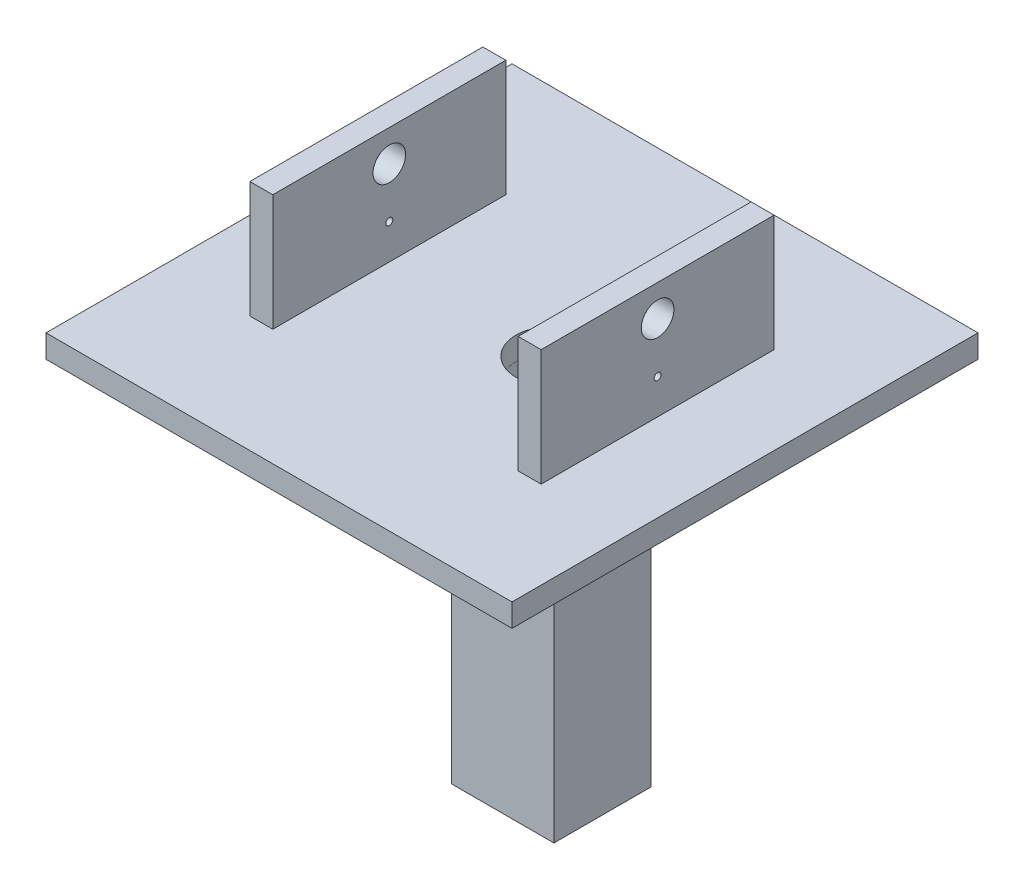
SolidWorks part; units mm, degrees
ref_plane "Front Plane" through (0, 0, 0) normal (0, 0, 1) x (1, 0, 0)
ref_plane "Top Plane" through (0, 0, 0) normal (0, 1, 0) x (1, 0, 0)
ref_plane "Right Plane" through (0, 0, 0) normal (1, 0, 0) x (0, 0, -1)
sketch "Sketch2" plane through (0, 0, 0) normal (0, 1, 0) x (1, 0, 0)
  line L1 (0, 0) -> (101.6, 0)
  line L2 (0, 0) -> (0, -101.6)
  line L3 (0, -101.6) -> (101.6, -101.6)
  line L4 (101.6, 0) -> (101.6, -101.6)
  dimension "D1" = 101.6
  dimension "D2" = 101.6
extrude "Boss-Extrude2" add sketch "Sketch2" along normal blind 5
sketch "Sketch3" plane through (0, 5, 0) normal (0, 1, 0) x (1, 0, 0)
  line L0 (0, 0) -> (0, -101.6) construction
  line L1 (19.05, -25.4) -> (24.05, -25.4)
  line L2 (19.05, -25.4) -> (19.05, -76.2)
  line L3 (19.05, -76.2) -> (24.05, -76.2)
  line L4 (24.05, -25.4) -> (24.05, -76.2)
  line L5 (0, -101.6) -> (101.6, -101.6) construction
  dimension "D1" = 5
  dimension "D2" = 19.05
  dimension "D3" = 50.8
  dimension "D4" = 25.4
extrude "Boss-Extrude3" add sketch "Sketch3" along normal blind 25.4
sketch "Sketch4" plane through (0, 5, 0) normal (0, 1, 0) x (1, 0, 0)
  line L0 (101.6, -101.6) -> (101.6, 0) construction
  line L1 (77.55, -25.4) -> (82.55, -25.4)
  line L2 (77.55, -25.4) -> (77.55, -76.2)
  line L3 (77.55, -76.2) -> (82.55, -76.2)
  line L4 (82.55, -25.4) -> (82.55, -76.2)
  line L5 (0, -101.6) -> (101.6, -101.6) construction
  dimension "D1" = 5
  dimension "D2" = 19.05
  dimension "D3" = 50.8
  dimension "D4" = 25.4
extrude "Boss-Extrude4" add sketch "Sketch4" along normal blind 25.4
sketch "Sketch8" plane through (19.05, 0, 0) normal (-1, 0, 0) x (0, 0, 1)
  line L0 (76.2, 30.4) -> (76.2, 5) construction
  line L1 (25.4, 5) -> (76.2, 5) construction
  circle A0 centre (50.8, 23.542) radius 3.556
  dimension "D1" = 25.4
  dimension "D2" = 18.542
extrude "Cut-Extrude1" cut sketch "Sketch8" against normal through all
sketch "Sketch9" plane through (82.55, 0, 0) normal (1, 0, 0) x (0, 0, -1)
  line L0 (-76.2, 30.4) -> (-76.2, 5) construction
  line L1 (-76.2, 5) -> (-25.4, 5) construction
  circle A0 centre (-50.8, 12.62) radius 0.762
  dimension "D1" = 25.4
  dimension "D2" = 7.62
extrude "Cut-Extrude2" cut sketch "Sketch9" against normal up to next
sketch "Sketch11" plane through (0, 5, 0) normal (0, 1, 0) x (1, 0, 0)
  line L0 (24.05, -76.2) -> (24.05, -25.4) construction
  line L1 (0, -101.6) -> (101.6, -101.6) construction
  circle A0 centre (59.61, -50.8) radius 7.9502
  dimension "D1" = 35.56
  dimension "D2" = 50.8
extrude "Cut-Extrude3" cut sketch "Sketch11" against normal through all
sketch "Sketch18" plane through (19.05, 0, 0) normal (-1, 0, 0) x (0, 0, 1)
  line L0 (0, 5) -> (101.6, 5) construction
  line L1 (25.4, 30.4) -> (25.4, 5) construction
  circle A0 centre (50.8, 12.62) radius 0.762
  dimension "D1" = 7.62
  dimension "D2" = 25.4
extrude "Cut-Extrude5" cut sketch "Sketch18" against normal up to next
sketch "Sketch19" plane through (0, 0, 0) normal (0, -1, 0) x (1, 0, 0)
  line L1 (48.1494, 61.3607) -> (70.4999, 61.3607)
  line L2 (48.1494, 61.3607) -> (48.1494, 40.1623)
  line L3 (48.1494, 40.1623) -> (70.4999, 40.1623)
  line L4 (70.4999, 61.3607) -> (70.4999, 40.1623)
extrude "Boss-Extrude5" add sketch "Sketch19" along normal blind 76.2
sketch "Sketch22" plane through (0, 0, 0) normal (0, 1, 0) x (1, 0, 0)
  circle A0 centre (59.61, -50.8) radius 7.94
extrude "Cut-Extrude7" cut sketch "Sketch22" against normal blind 72.2
sketch "Sketch23" plane through (0, -76.2, 0) normal (0, -1, 0) x (1, 0, 0)
  circle A0 centre (59.61, 50.8) radius 4.95
extrude "Cut-Extrude8" cut sketch "Sketch23" against normal through all
